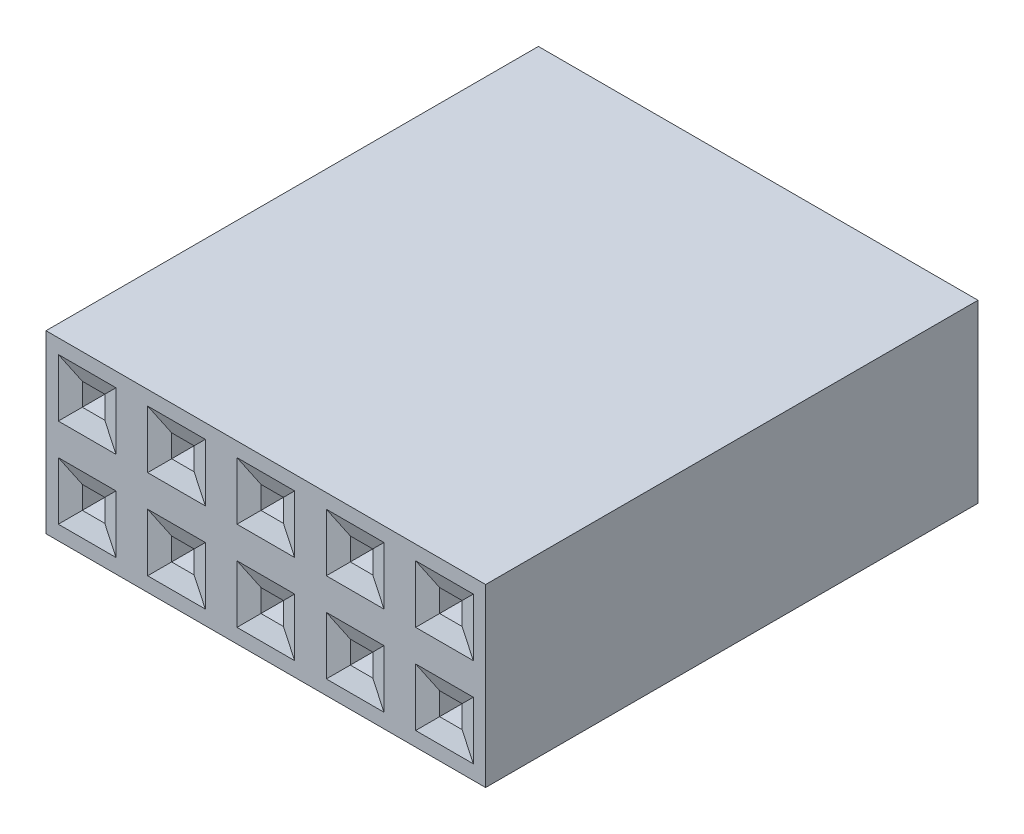
SolidWorks part; units mm, degrees
ref_plane "Front Plane" through (0, 0, 0) normal (0, 0, 1) x (1, 0, 0)
ref_plane "Top Plane" through (0, 0, 0) normal (0, 1, 0) x (1, 0, 0)
ref_plane "Right Plane" through (0, 0, 0) normal (1, 0, 0) x (0, 0, -1)
sketch "Sketch1" plane through (0, 0, 0) normal (0, 1, 0) x (1, 0, 0)
  line L1 (-6.25, 7) -> (6.25, 7)
  line L2 (-6.25, 7) -> (-6.25, -7)
  line L3 (-6.25, -7) -> (6.25, -7)
  line L4 (6.25, 7) -> (6.25, -7)
  line L5 (-6.25, 7) -> (6.25, -7) construction
  line L6 (-6.25, -7) -> (6.25, 7) construction
  point P0 (0, 0)
  dimension "D1" = 14
  dimension "D2" = 12.5
extrude "Boss-Extrude1" add sketch "Sketch1" along normal blind 5
sketch "Sketch3" plane through (0, 0, 7) normal (0, 0, 1) x (1, 0, 0)
  line L0 (-5.4, 0.91) -> (-5.4, 1.55) construction
  line L1 (-5.4, 1.55) -> (-4.76, 1.55) construction
  line L2 (-4.76, 0.91) -> (-5.4, 0.91) construction
  line L3 (-4.76, 1.55) -> (-4.76, 0.91) construction
  line L12 (-2.22, 0.91) -> (-2.86, 0.91) construction
  line L13 (-2.22, 1.55) -> (-2.22, 0.91) construction
  line L14 (-2.86, 1.55) -> (-2.22, 1.55) construction
  line L15 (-2.86, 0.91) -> (-2.86, 1.55) construction
  line L16 (0.32, 0.91) -> (-0.32, 0.91) construction
  line L17 (-0.32, 0.91) -> (-0.32, 1.55) construction
  line L18 (0.32, 1.55) -> (0.32, 0.91) construction
  line L19 (-0.32, 1.55) -> (0.32, 1.55) construction
  line L20 (2.86, 1.55) -> (2.86, 0.91) construction
  line L21 (2.22, 1.55) -> (2.86, 1.55) construction
  line L22 (2.86, 0.91) -> (2.22, 0.91) construction
  line L23 (2.22, 0.91) -> (2.22, 1.55) construction
  line L24 (5.4, 0.91) -> (4.76, 0.91) construction
  line L25 (4.76, 0.91) -> (4.76, 1.55) construction
  line L26 (5.4, 1.55) -> (5.4, 0.91) construction
  line L27 (4.76, 1.55) -> (5.4, 1.55) construction
  line L28 (5.4, 4.09) -> (5.4, 3.45) construction
  line L29 (4.76, 4.09) -> (5.4, 4.09) construction
  line L30 (5.4, 3.45) -> (4.76, 3.45) construction
  line L31 (4.76, 3.45) -> (4.76, 4.09) construction
  line L32 (2.86, 3.45) -> (2.22, 3.45) construction
  line L33 (2.22, 3.45) -> (2.22, 4.09) construction
  line L34 (0.32, 3.45) -> (-0.32, 3.45) construction
  line L35 (-0.32, 3.45) -> (-0.32, 4.09) construction
  line L36 (2.86, 4.09) -> (2.86, 3.45) construction
  line L37 (2.22, 4.09) -> (2.86, 4.09) construction
  line L38 (0.32, 4.09) -> (0.32, 3.45) construction
  line L39 (-0.32, 4.09) -> (0.32, 4.09) construction
  line L40 (-2.22, 4.09) -> (-2.22, 3.45) construction
  line L41 (-2.86, 4.09) -> (-2.22, 4.09) construction
  line L42 (-2.86, 3.45) -> (-2.86, 4.09) construction
  line L43 (-2.22, 3.45) -> (-2.86, 3.45) construction
  line L44 (-5.4, 3.45) -> (-5.4, 4.09) construction
  line L45 (-4.76, 3.45) -> (-5.4, 3.45) construction
  line L46 (-4.76, 4.09) -> (-4.76, 3.45) construction
  line L47 (-5.4, 4.09) -> (-4.76, 4.09) construction
  line L48 (-5.4, 0.91) -> (-5.4, 1.55)
  line L49 (-5.4, 1.55) -> (-4.76, 1.55)
  line L50 (-4.76, 0.91) -> (-5.4, 0.91)
  line L51 (-4.76, 1.55) -> (-4.76, 0.91)
  line L52 (-2.22, 0.91) -> (-2.86, 0.91)
  line L53 (-2.22, 1.55) -> (-2.22, 0.91)
  line L54 (-2.86, 1.55) -> (-2.22, 1.55)
  line L55 (-2.86, 0.91) -> (-2.86, 1.55)
  line L56 (0.32, 0.91) -> (-0.32, 0.91)
  line L57 (-0.32, 0.91) -> (-0.32, 1.55)
  line L58 (0.32, 1.55) -> (0.32, 0.91)
  line L59 (-0.32, 1.55) -> (0.32, 1.55)
  line L60 (2.86, 1.55) -> (2.86, 0.91)
  line L61 (2.22, 1.55) -> (2.86, 1.55)
  line L62 (2.86, 0.91) -> (2.22, 0.91)
  line L63 (2.22, 0.91) -> (2.22, 1.55)
  line L64 (5.4, 0.91) -> (4.76, 0.91)
  line L65 (4.76, 0.91) -> (4.76, 1.55)
  line L66 (5.4, 1.55) -> (5.4, 0.91)
  line L67 (4.76, 1.55) -> (5.4, 1.55)
  line L68 (5.4, 4.09) -> (5.4, 3.45)
  line L69 (4.76, 4.09) -> (5.4, 4.09)
  line L70 (5.4, 3.45) -> (4.76, 3.45)
  line L71 (4.76, 3.45) -> (4.76, 4.09)
  line L72 (2.86, 3.45) -> (2.22, 3.45)
  line L73 (2.22, 3.45) -> (2.22, 4.09)
  line L74 (0.32, 3.45) -> (-0.32, 3.45)
  line L75 (-0.32, 3.45) -> (-0.32, 4.09)
  line L76 (2.86, 4.09) -> (2.86, 3.45)
  line L77 (2.22, 4.09) -> (2.86, 4.09)
  line L78 (0.32, 4.09) -> (0.32, 3.45)
  line L79 (-0.32, 4.09) -> (0.32, 4.09)
  line L80 (-2.22, 4.09) -> (-2.22, 3.45)
  line L81 (-2.86, 4.09) -> (-2.22, 4.09)
  line L82 (-2.86, 3.45) -> (-2.86, 4.09)
  line L83 (-2.22, 3.45) -> (-2.86, 3.45)
  line L84 (-5.4, 3.45) -> (-5.4, 4.09)
  line L85 (-4.76, 3.45) -> (-5.4, 3.45)
  line L86 (-4.76, 4.09) -> (-4.76, 3.45)
  line L87 (-5.4, 4.09) -> (-4.76, 4.09)
extrude "Cut-Extrude1" cut sketch "Sketch3" against normal up to surface (4.5 mm away)
chamfer "Chamfer1" distance 0.5 angle 20 40 edges at (-5.4, 1.23, 7) (-5.08, 0.91, 7) (-4.76, 1.23, 7) (-5.08, 1.55, 7) (-2.22, 1.23, 7) (-2.54, 0.91, 7) (-2.86, 1.23, 7) (-2.54, 1.55, 7) (-0.32, 1.23, 7) (0, 0.91, 7) (0.32, 1.23, 7) (0, 1.55, 7) (2.22, 1.23, 7) (2.54, 0.91, 7) (2.86, 1.23, 7) (2.54, 1.55, 7) (4.76, 1.23, 7) (5.08, 0.91, 7) (5.4, 1.23, 7) (5.08, 1.55, 7) (4.76, 3.77, 7) (5.08, 3.45, 7) (5.4, 3.77, 7) (5.08, 4.09, 7) (2.54, 3.45, 7) (2.86, 3.77, 7) (2.22, 3.77, 7) (2.54, 4.09, 7) (0.32, 3.77, 7) (0, 3.45, 7) (-0.32, 3.77, 7) (0, 4.09, 7) (-2.22, 3.77, 7) (-2.54, 4.09, 7) (-2.86, 3.77, 7) (-2.54, 3.45, 7) (-5.4, 3.77, 7) (-5.08, 4.09, 7) (-4.76, 3.77, 7) (-5.08, 3.45, 7)
sketch "Sketch4" plane through (0, 0, -7) normal (0, 0, -1) x (-1, 0, 0)
  line L0 (-4.26, 2.05) -> (-5.9, 2.05) construction
  line L1 (-5.9, 2.05) -> (-5.9, 0.41) construction
  line L2 (-5.9, 0.41) -> (-4.26, 0.41) construction
  line L3 (-4.26, 0.41) -> (-4.26, 2.05) construction
  line L4 (-3.36, 0.41) -> (-1.72, 0.41) construction
  line L5 (-1.72, 0.41) -> (-1.72, 2.05) construction
  line L6 (-1.72, 2.05) -> (-3.36, 2.05) construction
  line L7 (-3.36, 2.05) -> (-3.36, 0.41) construction
  line L8 (-0.82, 2.05) -> (-0.82, 0.41) construction
  line L9 (-0.82, 0.41) -> (0.82, 0.41) construction
  line L10 (0.82, 0.41) -> (0.82, 2.05) construction
  line L11 (0.82, 2.05) -> (-0.82, 2.05) construction
  line L12 (3.36, 2.05) -> (1.72, 2.05) construction
  line L13 (1.72, 2.05) -> (1.72, 0.41) construction
  line L14 (1.72, 0.41) -> (3.36, 0.41) construction
  line L15 (3.36, 0.41) -> (3.36, 2.05) construction
  line L16 (4.26, 0.41) -> (5.9, 0.41) construction
  line L17 (5.9, 0.41) -> (5.9, 2.05) construction
  line L18 (4.26, 2.05) -> (4.26, 0.41) construction
  line L19 (5.9, 2.05) -> (4.26, 2.05) construction
  line L20 (4.26, 2.95) -> (5.9, 2.95) construction
  line L21 (5.9, 2.95) -> (5.9, 4.59) construction
  line L22 (5.9, 4.59) -> (4.26, 4.59) construction
  line L23 (4.26, 4.59) -> (4.26, 2.95) construction
  line L24 (1.72, 2.95) -> (3.36, 2.95) construction
  line L25 (3.36, 2.95) -> (3.36, 4.59) construction
  line L26 (3.36, 4.59) -> (1.72, 4.59) construction
  line L27 (1.72, 4.59) -> (1.72, 2.95) construction
  line L28 (-0.82, 2.95) -> (0.82, 2.95) construction
  line L29 (0.82, 2.95) -> (0.82, 4.59) construction
  line L30 (0.82, 4.59) -> (-0.82, 4.59) construction
  line L31 (-0.82, 4.59) -> (-0.82, 2.95) construction
  line L32 (-3.36, 2.95) -> (-1.72, 2.95) construction
  line L33 (-1.72, 2.95) -> (-1.72, 4.59) construction
  line L34 (-1.72, 4.59) -> (-3.36, 4.59) construction
  line L35 (-3.36, 4.59) -> (-3.36, 2.95) construction
  line L36 (-5.9, 2.95) -> (-4.26, 2.95) construction
  line L37 (-5.9, 4.59) -> (-5.9, 2.95) construction
  line L38 (-4.26, 2.95) -> (-4.26, 4.59) construction
  line L39 (-4.26, 4.59) -> (-5.9, 4.59) construction
  line L40 (-4.26, 2.05) -> (-5.9, 2.05)
  line L41 (-5.9, 2.05) -> (-5.9, 0.41)
  line L42 (-5.9, 0.41) -> (-4.26, 0.41)
  line L43 (-4.26, 0.41) -> (-4.26, 2.05)
  line L44 (-3.36, 0.41) -> (-1.72, 0.41)
  line L45 (-1.72, 0.41) -> (-1.72, 2.05)
  line L46 (-1.72, 2.05) -> (-3.36, 2.05)
  line L47 (-3.36, 2.05) -> (-3.36, 0.41)
  line L48 (-0.82, 2.05) -> (-0.82, 0.41)
  line L49 (-0.82, 0.41) -> (0.82, 0.41)
  line L50 (0.82, 0.41) -> (0.82, 2.05)
  line L51 (0.82, 2.05) -> (-0.82, 2.05)
  line L52 (3.36, 2.05) -> (1.72, 2.05)
  line L53 (1.72, 2.05) -> (1.72, 0.41)
  line L54 (1.72, 0.41) -> (3.36, 0.41)
  line L55 (3.36, 0.41) -> (3.36, 2.05)
  line L56 (4.26, 0.41) -> (5.9, 0.41)
  line L57 (5.9, 0.41) -> (5.9, 2.05)
  line L58 (4.26, 2.05) -> (4.26, 0.41)
  line L59 (5.9, 2.05) -> (4.26, 2.05)
  line L60 (4.26, 2.95) -> (5.9, 2.95)
  line L61 (5.9, 2.95) -> (5.9, 4.59)
  line L62 (5.9, 4.59) -> (4.26, 4.59)
  line L63 (4.26, 4.59) -> (4.26, 2.95)
  line L64 (1.72, 2.95) -> (3.36, 2.95)
  line L65 (3.36, 2.95) -> (3.36, 4.59)
  line L66 (3.36, 4.59) -> (1.72, 4.59)
  line L67 (1.72, 4.59) -> (1.72, 2.95)
  line L68 (-0.82, 2.95) -> (0.82, 2.95)
  line L69 (0.82, 2.95) -> (0.82, 4.59)
  line L70 (0.82, 4.59) -> (-0.82, 4.59)
  line L71 (-0.82, 4.59) -> (-0.82, 2.95)
  line L72 (-3.36, 2.95) -> (-1.72, 2.95)
  line L73 (-1.72, 2.95) -> (-1.72, 4.59)
  line L74 (-1.72, 4.59) -> (-3.36, 4.59)
  line L75 (-3.36, 4.59) -> (-3.36, 2.95)
  line L76 (-5.9, 2.95) -> (-4.26, 2.95)
  line L77 (-5.9, 4.59) -> (-5.9, 2.95)
  line L78 (-4.26, 2.95) -> (-4.26, 4.59)
  line L79 (-4.26, 4.59) -> (-5.9, 4.59)
extrude "Cut-Extrude2" cut sketch "Sketch4" against normal blind 6
